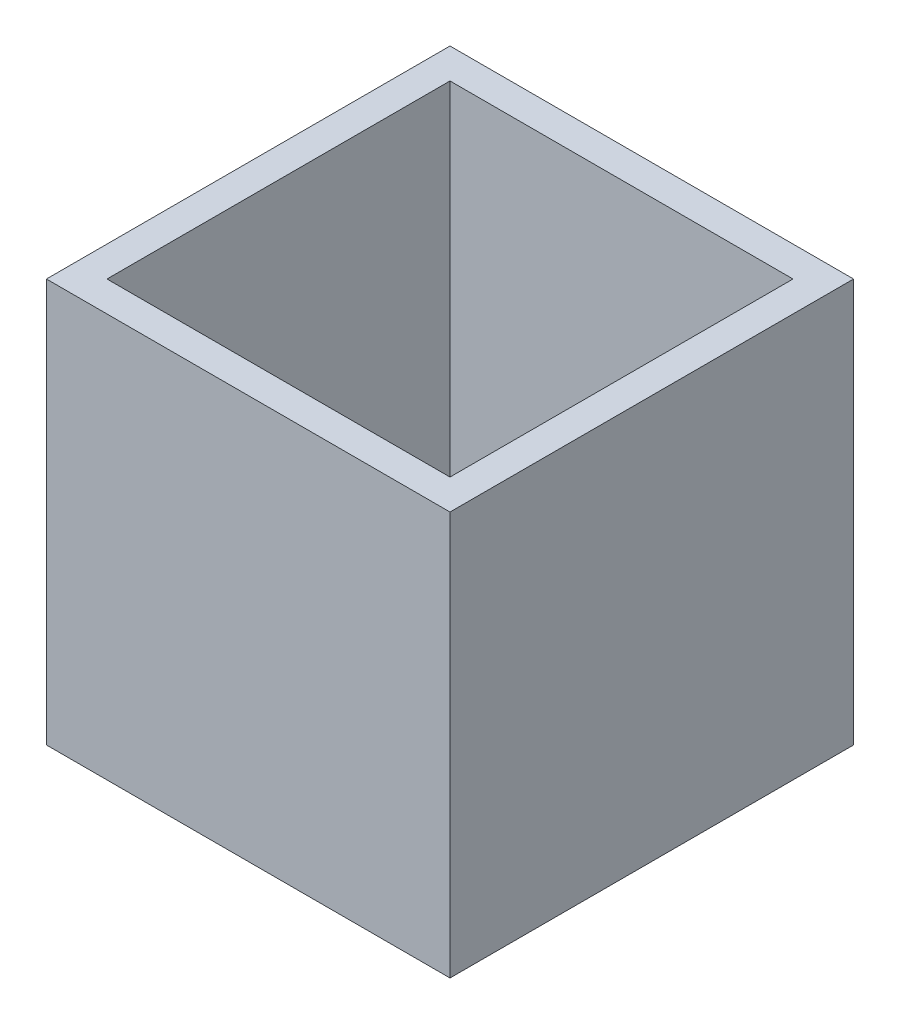
SolidWorks part; units mm, degrees
ref_plane "Front Plane" through (0, 0, 0) normal (0, 0, 1) x (1, 0, 0)
ref_plane "Top Plane" through (0, 0, 0) normal (0, 1, 0) x (1, 0, 0)
ref_plane "Right Plane" through (0, 0, 0) normal (1, 0, 0) x (0, 0, -1)
sketch "Sketch1" plane through (0, 0, 0) normal (0, 1, 0) x (1, 0, 0)
  line L1 (0, 0) -> (-20, 0)
  line L2 (0, 0) -> (0, 20)
  line L3 (0, 20) -> (-20, 20)
  line L4 (-20, 0) -> (-20, 20)
  dimension "D1" = 20
  dimension "D2" = 20
extrude "Boss-Extrude1" add sketch "Sketch1" along normal blind 20
shell "Shell1" thickness 1.5
sketch "Sketch2" plane through (0, 0, 0) normal (0, -1, 0) x (1, 0, 0)
  circle A0 centre (-13.147, -8.4014) radius 5
  circle A1 centre (-9.4179, -15.1041) radius 0.75
  circle A2 centre (-4.9667, -11.7178) radius 3
  dimension "D1" = 10
  dimension "D2" = 1.5
  dimension "D3" = 6
extrude "Cut-Extrude1" cut sketch "Sketch2" against normal through all
